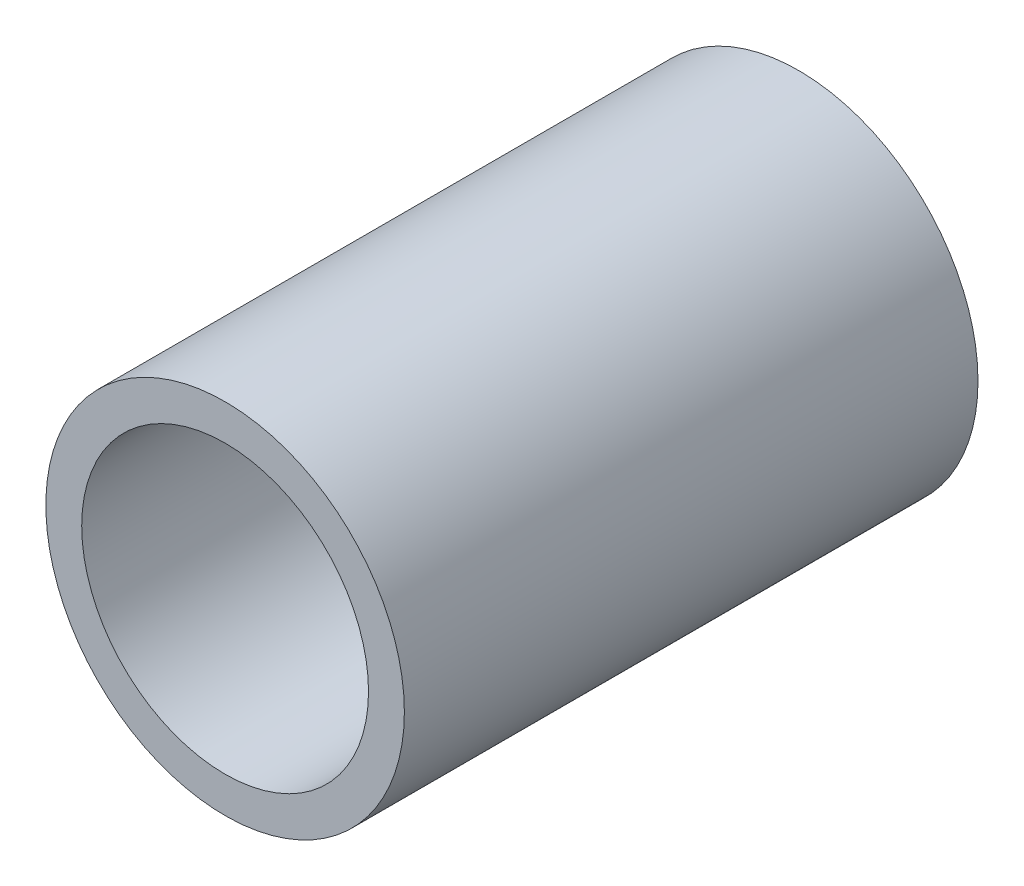
SolidWorks part; units mm, degrees
material "Brass"
ref_plane "Front" through (0, 0, 0) normal (0, 0, 1) x (1, 0, 0)
ref_plane "Top" through (0, 0, 0) normal (0, 1, 0) x (1, 0, 0)
ref_plane "Right" through (0, 0, 0) normal (1, 0, 0) x (0, 0, -1)
sketch "Sketch1" plane through (0, 0, 0) normal (0, 0, 1) x (1, 0, 0)
  circle A0 centre (0, 0) radius 7.9375
  circle A1 centre (0, 0) radius 6.35
  dimension "D1" = 15.875
  dimension "D2" = 12.7
extrude "Extrude1" add sketch "Sketch1" along normal blind 25.4
